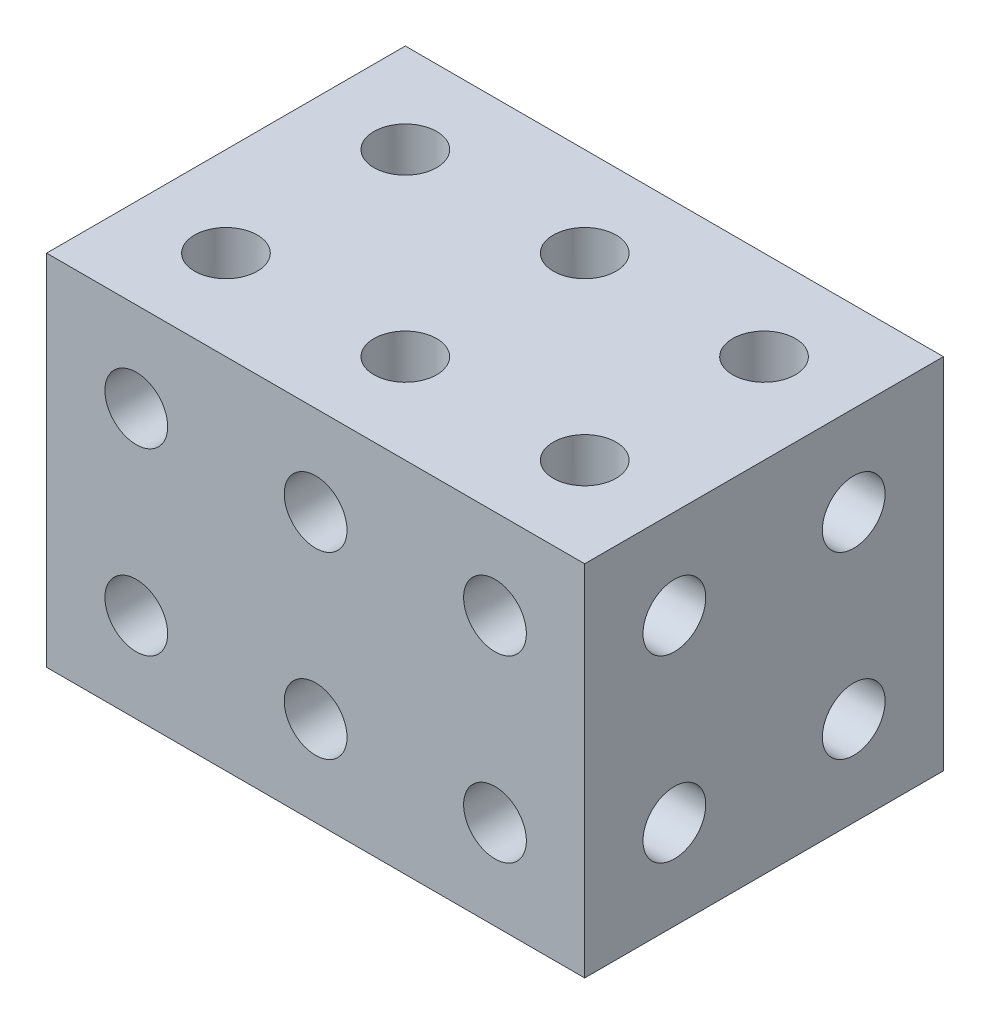
SolidWorks part; units mm, degrees
ref_plane "Plan de face" through (0, 0, 0) normal (0, 0, 1) x (1, 0, 0)
ref_plane "Plan de dessus" through (0, 0, 0) normal (0, 1, 0) x (1, 0, 0)
ref_plane "Plan de droite" through (0, 0, 0) normal (1, 0, 0) x (0, 0, -1)
sketch "Esquisse1" plane through (0, 0, 0) normal (1, 0, 0) x (0, 0, -1)
  line L1 (0, 0) -> (20, 0)
  line L2 (0, 0) -> (0, 20)
  line L3 (0, 20) -> (20, 20)
  line L4 (20, 0) -> (20, 20)
  dimension "D1" = 20
  dimension "D2" = 20
extrude "Boss.-Extru.1" add sketch "Esquisse1" along normal blind 30
sketch "Esquisse2" plane through (0, 20, 0) normal (0, 1, 0) x (1, 0, 0)
  line L0 (0, 15) -> (40, 15) construction
  line L4 (30, 20) -> (0, 20) construction
  circle A0 centre (5, 15) radius 1.75
  circle A1 centre (15, 15) radius 1.75
  circle A2 centre (25, 15) radius 1.75
  circle A3 centre (35, 15) radius 1.75
  circle A4 centre (5, 5) radius 1.75
  circle A5 centre (15, 5) radius 1.75
  circle A6 centre (25, 5) radius 1.75
  circle A7 centre (35, 5) radius 1.75
  circle A8 centre (5, -5) radius 1.75
  circle A9 centre (15, -5) radius 1.75
  circle A10 centre (25, -5) radius 1.75
  circle A11 centre (35, -5) radius 1.75
  circle A12 centre (5, -15) radius 1.75
  circle A13 centre (15, -15) radius 1.75
  circle A14 centre (25, -15) radius 1.75
  circle A15 centre (35, -15) radius 1.75
  dimension "D4" = 3.5
  dimension "D1" = 5
  dimension "D2" = 10
  dimension "D3" = 10
  dimension "D5" = 10
  dimension "D6" = 5
  dimension "D7" = 4
extrude "Enlèv. mat.-Extru.1" cut sketch "Esquisse2" against normal through all
sketch "Esquisse3" plane through (0, 0, 0) normal (0, 0, 1) x (1, 0, 0)
  line L0 (0, 15) -> (40, 15) construction
  line L1 (0, 20) -> (0, 0) construction
  line L3 (30, 20) -> (0, 20) construction
  circle A0 centre (5, 15) radius 1.75
  circle A1 centre (15, 15) radius 1.75
  circle A2 centre (25, 15) radius 1.75
  circle A3 centre (35, 15) radius 1.75
  circle A4 centre (5, 5) radius 1.75
  circle A5 centre (15, 5) radius 1.75
  circle A6 centre (25, 5) radius 1.75
  circle A7 centre (35, 5) radius 1.75
  dimension "D4" = 3.5
  dimension "D1" = 5
  dimension "D2" = 10
  dimension "D3" = 10
  dimension "D5" = 10
  dimension "D6" = 5
  dimension "D7" = 2
extrude "Enlèv. mat.-Extru.2" cut sketch "Esquisse3" against normal blind 40
sketch "Esquisse4" plane through (30, 0, 0) normal (1, 0, 0) x (0, 0, -1)
  line L0 (0, 15) -> (20, 15) construction
  line L1 (0, 20) -> (0, 0) construction
  line L3 (20, 20) -> (0, 20) construction
  circle A0 centre (5, 15) radius 1.75
  circle A1 centre (15, 15) radius 1.75
  circle A2 centre (25, 15) radius 1.75
  circle A3 centre (35, 15) radius 1.75
  circle A4 centre (5, 5) radius 1.75
  circle A5 centre (15, 5) radius 1.75
  dimension "D1" = 3.5
  dimension "D2" = 5
  dimension "D4" = 5
  dimension "D3" = 4
  dimension "D5" = 2
extrude "Enlèv. mat.-Extru.3" cut sketch "Esquisse4" against normal blind 40
